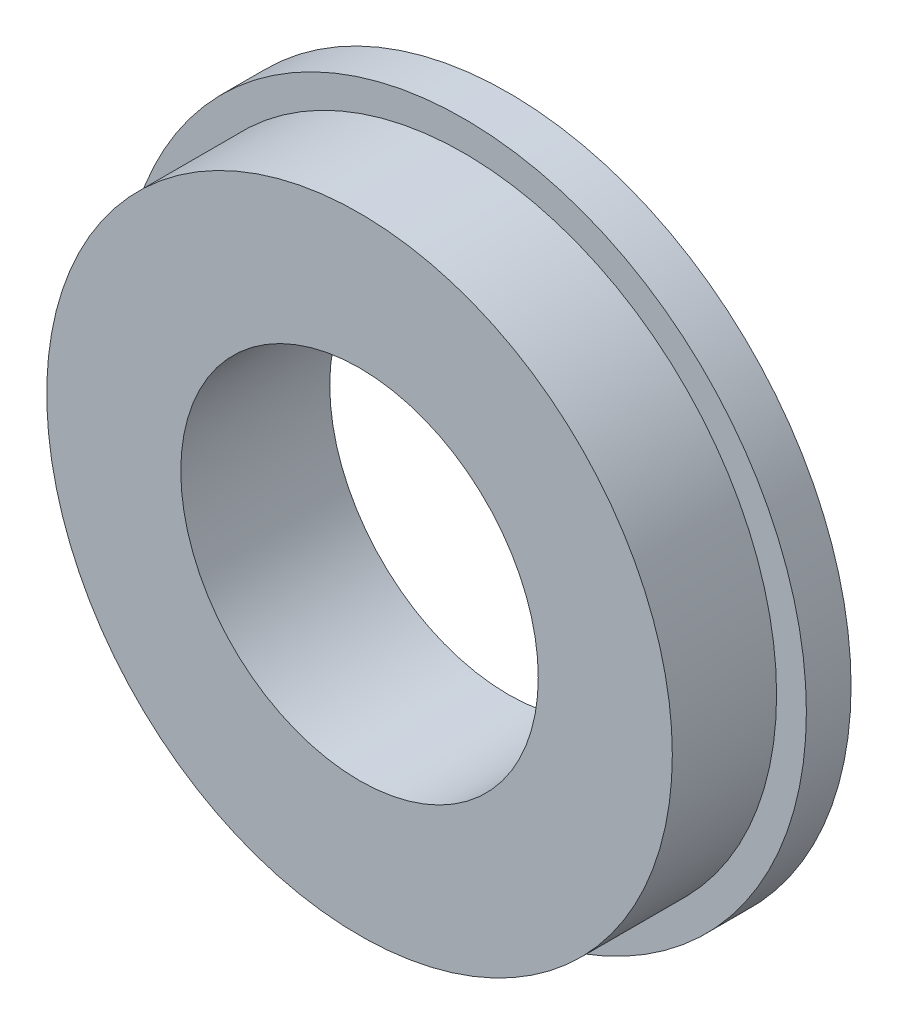
SolidWorks part; units mm, degrees
material "6061 合金"
ref_plane "前视基准面" through (0, 0, 0) normal (0, 0, 1) x (1, 0, 0)
ref_plane "上视基准面" through (0, 0, 0) normal (0, 1, 0) x (1, 0, 0)
ref_plane "右视基准面" through (0, 0, 0) normal (1, 0, 0) x (0, 0, -1)
sketch "草图1" plane through (0, 0, 0) normal (0, 0, 1) x (1, 0, 0)
  circle A0 centre (0, 0) radius 11.5
  dimension "D1" = 23
extrude "凸台-拉伸1" add sketch "草图1" along normal blind 1.5
sketch "草图2" plane through (0, 0, 1.5) normal (0, 0, 1) x (1, 0, 0)
  circle A0 centre (0, 0) radius 10.5
  dimension "D1" = 21
extrude "凸台-拉伸2" add sketch "草图2" along normal blind 3.5
sketch "草图3" plane through (0, 0, 5) normal (0, 0, 1) x (1, 0, 0)
  circle A0 centre (0, 0) radius 6
  dimension "D1" = 12
extrude "切除-拉伸1" cut sketch "草图3" against normal through all
